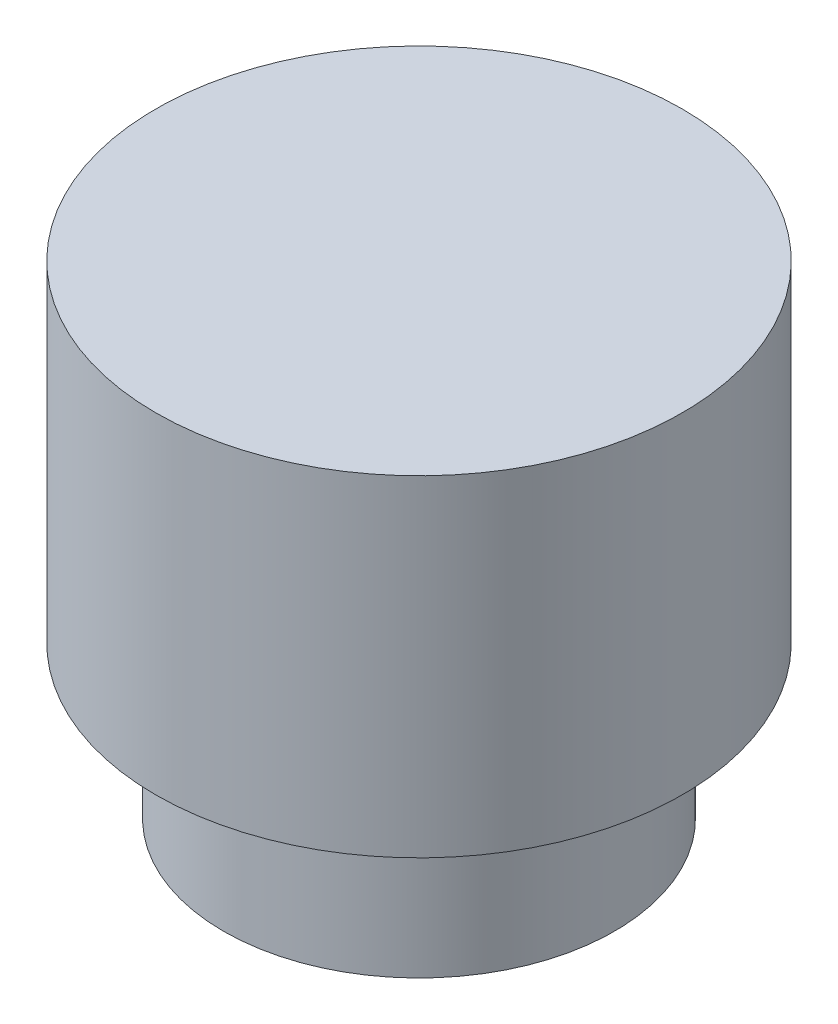
SolidWorks part; units mm, degrees
ref_plane "Front Plane" through (0, 0, 0) normal (0, 0, 1) x (1, 0, 0)
ref_plane "Top Plane" through (0, 0, 0) normal (0, 1, 0) x (1, 0, 0)
ref_plane "Right Plane" through (0, 0, 0) normal (1, 0, 0) x (0, 0, -1)
sketch "Sketch1" plane through (0, 0, 0) normal (0, 1, 0) x (1, 0, 0)
  circle A0 centre (0, 0) radius 1.75
  dimension "D1" = 3.5
extrude "Boss-Extrude1" add sketch "Sketch1" against normal blind 2.2
sketch "Sketch2" plane through (0, -2.2, 0) normal (0, -1, 0) x (1, 0, 0)
  circle A0 centre (0, 0) radius 1.3
  dimension "D1" = 2.6
extrude "Boss-Extrude2" add sketch "Sketch2" along normal blind 1.01
